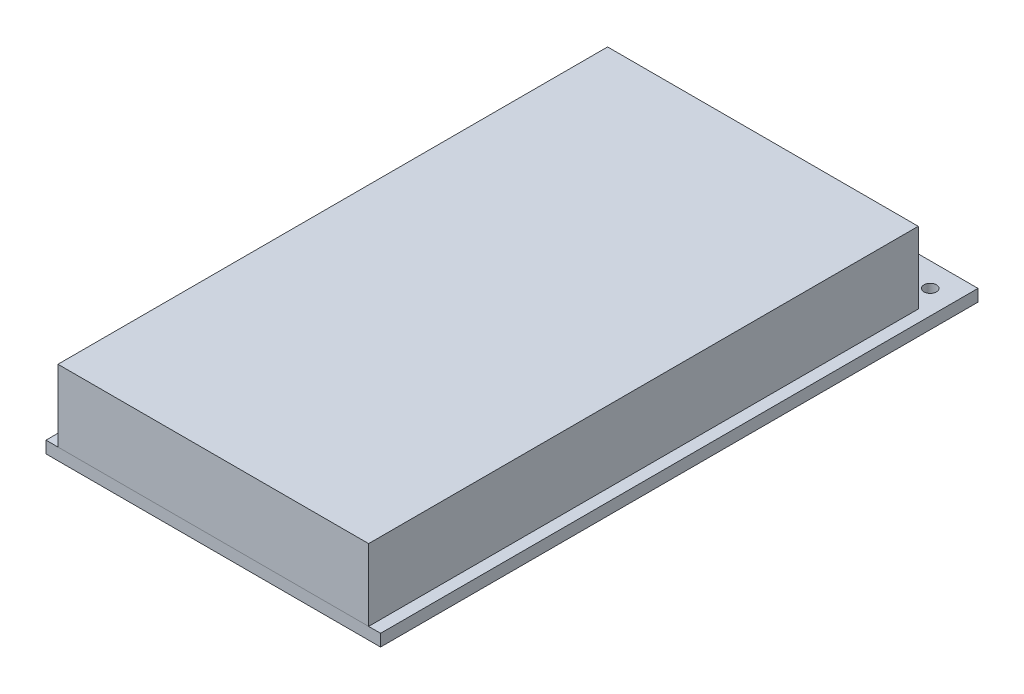
SolidWorks part; units mm, degrees
material "Balsa"
ref_plane "Front Plane" through (0, 0, 0) normal (0, 0, 1) x (1, 0, 0)
ref_plane "Top Plane" through (0, 0, 0) normal (0, 1, 0) x (1, 0, 0)
ref_plane "Right Plane" through (0, 0, 0) normal (1, 0, 0) x (0, 0, -1)
sketch "Sketch1" plane through (0, 0, 0) normal (0, 1, 0) x (1, 0, 0)
  line L1 (-88.9, 158.75) -> (88.9, 158.75)
  line L2 (-88.9, 158.75) -> (-88.9, -158.75)
  line L3 (-88.9, -158.75) -> (88.9, -158.75)
  line L4 (88.9, 158.75) -> (88.9, -158.75)
  line L5 (-88.9, 158.75) -> (88.9, -158.75) construction
  line L6 (-88.9, -158.75) -> (88.9, 158.75) construction
  point P0 (0, 0)
  dimension "D1" = 177.8
  dimension "D2" = 317.5
extrude "Boss-Extrude1" add sketch "Sketch1" along normal blind 6.35
sketch "Sketch2" plane through (0, 6.35, 0) normal (0, 1, 0) x (1, 0, 0)
  line L0 (-88.9, -158.75) -> (88.9, -158.75) construction
  line L5 (-82.55, -158.75) -> (82.55, -158.75)
  line L6 (-82.55, -158.75) -> (-82.55, 133.35)
  line L7 (-82.55, 133.35) -> (82.55, 133.35)
  line L8 (82.55, -158.75) -> (82.55, 133.35)
  line L9 (0, 133.35) -> (0, -158.75) construction
  line L10 (-82.55, -12.7) -> (82.55, -12.7) construction
  point P334 (0, -12.7)
  dimension "D1" = 292.1
  dimension "D2" = 165.1
extrude "Boss-Extrude2" add sketch "Sketch2" along normal blind 38.1 separate body
sketch "Sketch3" plane through (0, 0, 0) normal (0, -1, 0) x (1, 0, 0)
  line L0 (88.9, -158.75) -> (-88.9, -158.75) construction
  line L1 (-76.2, 146.05) -> (76.2, 146.05) construction
  line L2 (-76.2, 146.05) -> (-76.2, -146.05) construction
  line L3 (-76.2, -146.05) -> (76.2, -146.05) construction
  line L4 (76.2, 146.05) -> (76.2, -146.05) construction
  line L5 (-76.2, 146.05) -> (76.2, -146.05) construction
  line L6 (-76.2, -146.05) -> (76.2, 146.05) construction
  line L7 (88.9, 158.75) -> (88.9, -158.75) construction
  circle A0 centre (76.2, -146.05) radius 3.302
  circle A1 centre (-76.2, -146.05) radius 3.302
  circle A2 centre (-76.2, 146.05) radius 3.302 construction
  circle A3 centre (76.2, 146.05) radius 3.302 construction
  point P0 (0, 0)
  dimension "D3" = 6.604
  dimension "D1" = 12.7
  dimension "D2" = 12.7
extrude "Cut-Extrude1" cut sketch "Sketch3" against normal through all both and the other way through all
